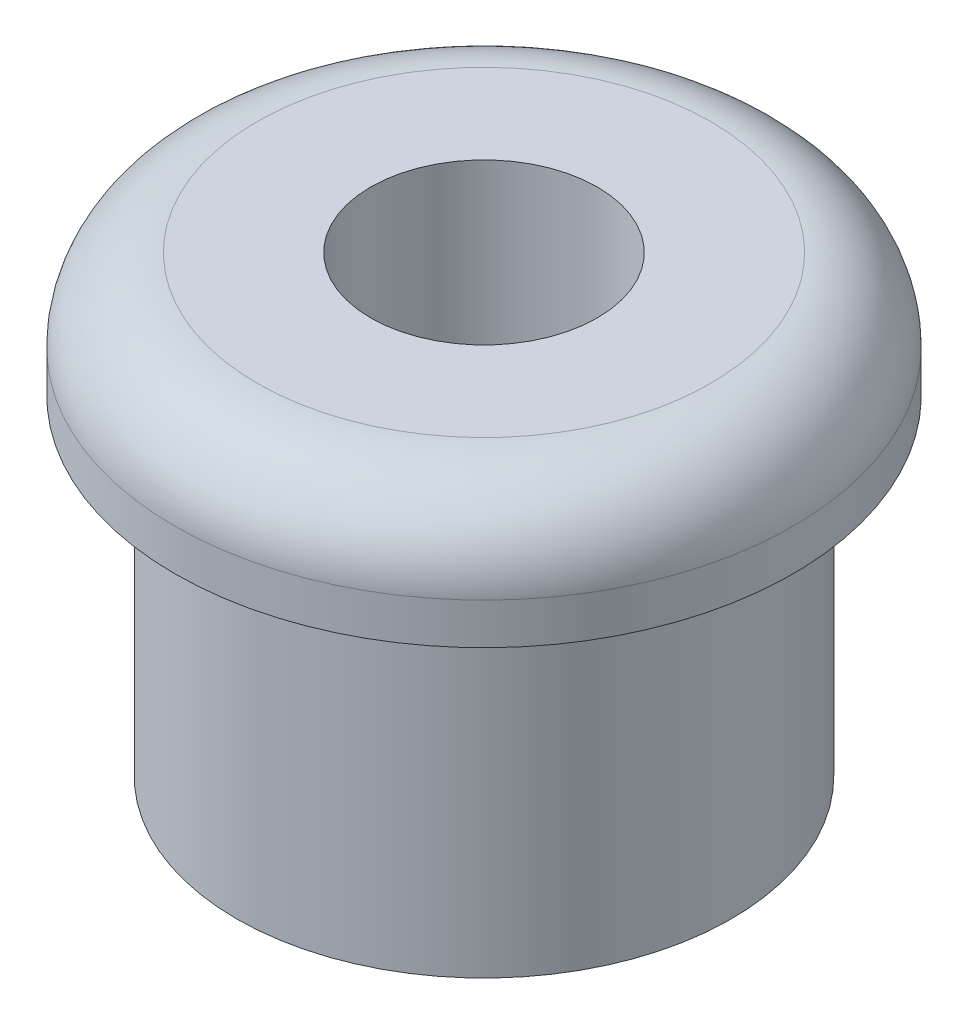
SolidWorks part; units mm, degrees
material "ABS"
ref_plane "Front Plane" through (0, 0, 0) normal (0, 0, 1) x (1, 0, 0)
ref_plane "Top Plane" through (0, 0, 0) normal (0, 1, 0) x (1, 0, 0)
ref_plane "Right Plane" through (0, 0, 0) normal (1, 0, 0) x (0, 0, -1)
sketch "Sketch1" plane through (0, 0, 0) normal (0, 1, 0) x (1, 0, 0)
  circle A0 centre (0, 0) radius 2.75
  circle A1 centre (0, 0) radius 6
  dimension "D1" = 5.5
  dimension "D2" = 12
extrude "Boss-Extrude1" add sketch "Sketch1" along normal blind 8
sketch "Sketch2" plane through (0, 8, 0) normal (0, 1, 0) x (1, 0, 0)
  circle A0 centre (0, 0) radius 7.5
  circle A1 centre (0, 0) radius 2.75 construction
  circle A2 centre (0, 0) radius 2.75
  dimension "D1" = 15
extrude "Boss-Extrude2" add sketch "Sketch2" along normal blind 3
fillet "Fillet1" radius 2 1 edges at (0, 11, 7.5)
